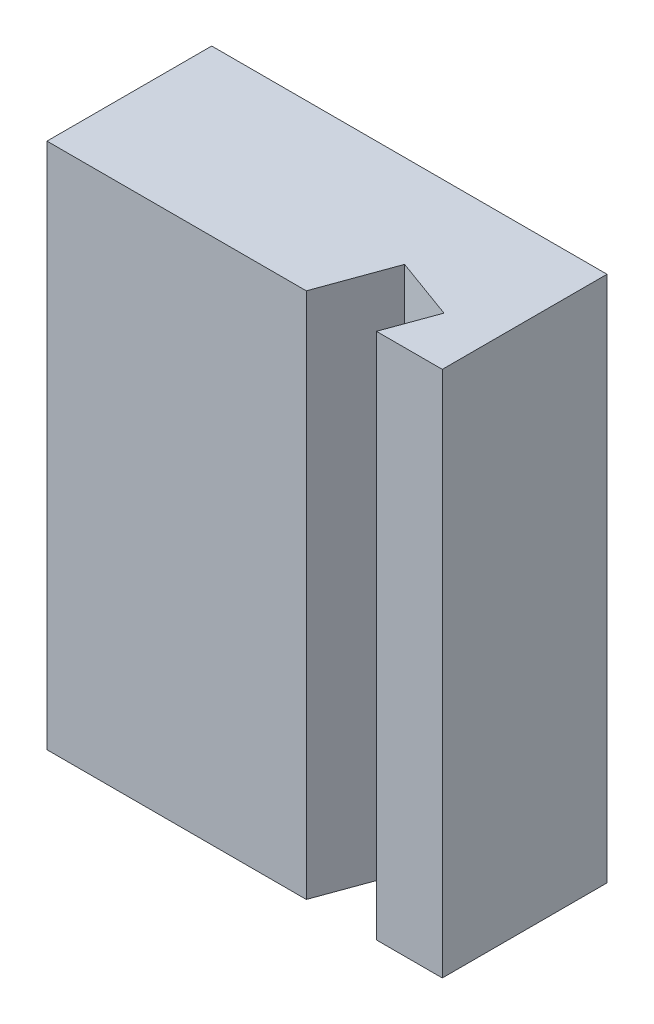
SolidWorks part; units mm, degrees
ref_plane "Front Plane" through (0, 0, 0) normal (1, 0, 0) x (0, 1, 0)
ref_plane "Top Plane" through (0, 0, 0) normal (0, 0, 1) x (0, 1, 0)
ref_plane "Right Plane" through (0, 0, 0) normal (0, 1, 0) x (-1, 0, 0)
sketch "Sketch1" plane through (0, 0, 0) normal (0, 1, 0) x (-1, 0, 0)
  line L0 (-20, 12.5) -> (-22.7362, 4.9825)
  line L1 (30, 12.5) -> (-9.3582, 12.5)
  line L2 (30, 12.5) -> (30, -12.5)
  line L3 (30, -12.5) -> (-30, -12.5)
  line L4 (-30, 12.5) -> (-30, -12.5)
  line L5 (30, 12.5) -> (-30, -12.5) construction
  line L6 (30, -12.5) -> (-30, 12.5) construction
  line L7 (-22.7362, 4.9825) -> (-13.3392, 1.5623)
  line L8 (-13.3392, 1.5623) -> (-9.3582, 12.5)
  line L9 (-20, 12.5) -> (-30, 12.5)
  point P0 (0, 0)
  dimension "D1" = 25
  dimension "D2" = 60
  dimension "D3" = 10
  dimension "D4" = 8
  dimension "D5" = 20
  dimension "D6" = 10
extrude "Boss-Extrude1" add sketch "Sketch1" along normal mid plane 80
sketch "Sketch2" plane through (12.2809, 0, 4.4699) normal (0.9397, 0, 0.342) x (0, 1, 0)
  line L1 (-40, -3.0942) -> (90, -3.0942)
  line L2 (-40, -3.0942) -> (-40, 126.9058)
  line L3 (-40, 126.9058) -> (90, 126.9058)
  line L4 (90, -3.0942) -> (90, 126.9058)
  dimension "D1" = 130
  dimension "D2" = 130
